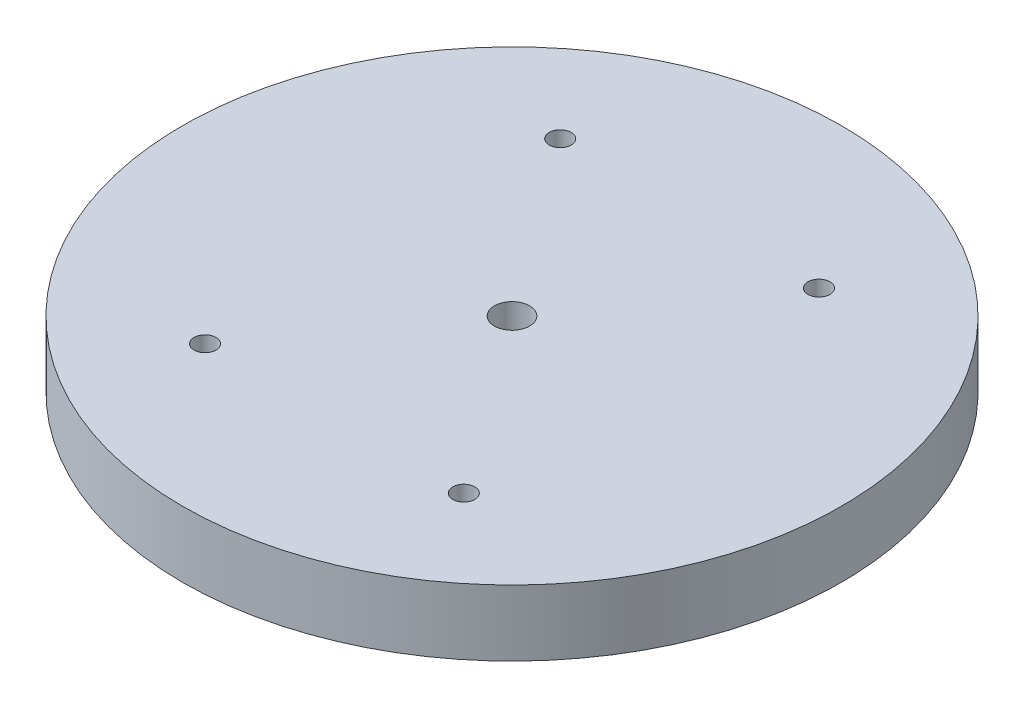
SolidWorks part; units mm, degrees
ref_plane "Front Plane" through (0, 0, 0) normal (0, 0, 1) x (1, 0, 0)
ref_plane "Top Plane" through (0, 0, 0) normal (0, 1, 0) x (1, 0, 0)
ref_plane "Right Plane" through (0, 0, 0) normal (1, 0, 0) x (0, 0, -1)
sketch "Sketch1" plane through (0, 0, 0) normal (0, 1, 0) x (1, 0, 0)
  line L0 (0, 0) -> (83.5355, 0) construction
  line L1 (0, 0) -> (0, 87.1124) construction
  circle A0 centre (0, 0) radius 75
  circle A1 centre (29.4436, 40.4113) radius 2.5
  circle A2 centre (29.4436, -40.4113) radius 2.5
  circle A3 centre (-29.4436, -40.4113) radius 2.5
  circle A4 centre (-29.4436, 40.4113) radius 2.5
  dimension "D1" = 150
  dimension "D2" = 5
  dimension "D3" = 50
extrude "Boss-Extrude1" add sketch "Sketch1" along normal blind 15
sketch "Sketch2" plane through (0, 15, 0) normal (0, 1, 0) x (1, 0, 0)
  circle A0 centre (0, 0) radius 4
  dimension "D1" = 8
extrude "Cut-Extrude1" cut sketch "Sketch2" against normal blind 24
